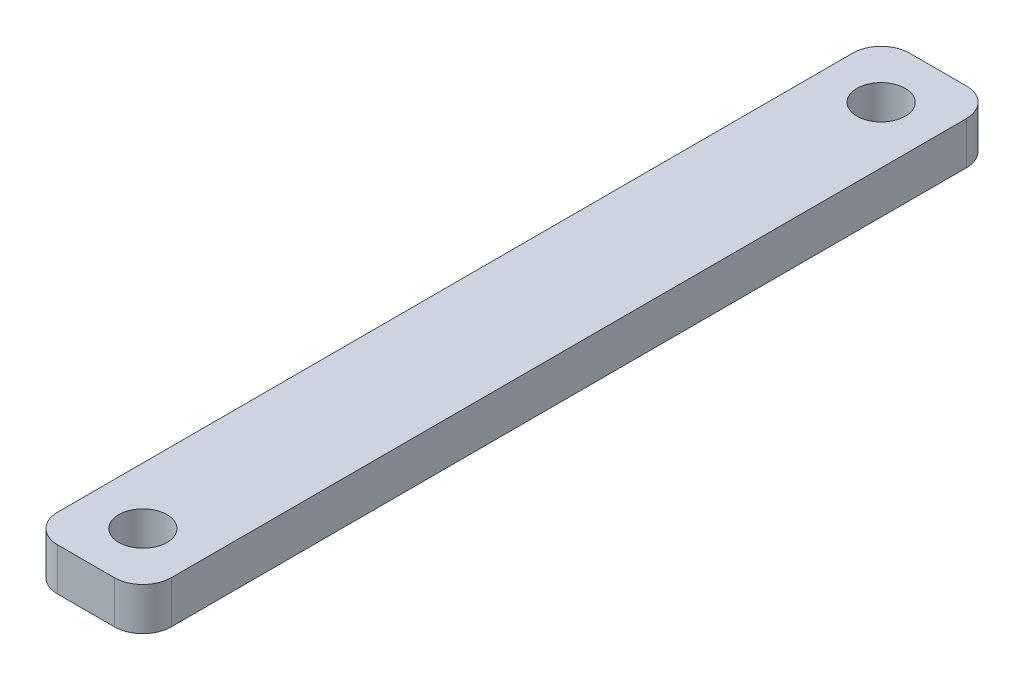
SolidWorks part; units mm, degrees
ref_plane "前基準面" through (0, 0, 0) normal (0, 0, 1) x (1, 0, 0)
ref_plane "上基準面" through (0, 0, 0) normal (0, 1, 0) x (1, 0, 0)
ref_plane "右基準面" through (0, 0, 0) normal (1, 0, 0) x (0, 0, -1)
sketch "草圖1" plane through (0, 0, 0) normal (0, 1, 0) x (1, 0, 0)
  line L0 (0, 30) -> (0, -30) construction
  line L1 (-2, 30) -> (2, 30)
  line L2 (-4, 28) -> (-4, -28)
  line L3 (-2, -30) -> (2, -30)
  line L4 (4, 28) -> (4, -28)
  line L5 (-4, 30) -> (4, -30) construction
  line L6 (-4, -30) -> (4, 30) construction
  line L7 (-4, 0) -> (4, 0) construction
  arc A0 (2, -30) -> (4, -28) centre (2, -28) ccw
  arc A1 (-4, -28) -> (-2, -30) centre (-2, -28) ccw
  arc A2 (2, 30) -> (4, 28) centre (2, 28) cw
  arc A3 (-2, 30) -> (-4, 28) centre (-2, 28) ccw
  circle A4 centre (0, 26) radius 1.7
  circle A5 centre (0, -26) radius 1.7
  point P0 (0, 0)
  dimension "D3" = 2
  dimension "D4" = 3.4
  dimension "D1" = 60
  dimension "D2" = 8
  dimension "D5" = 4
extrude "填料-伸長1" add sketch "草圖1" along normal blind 3
